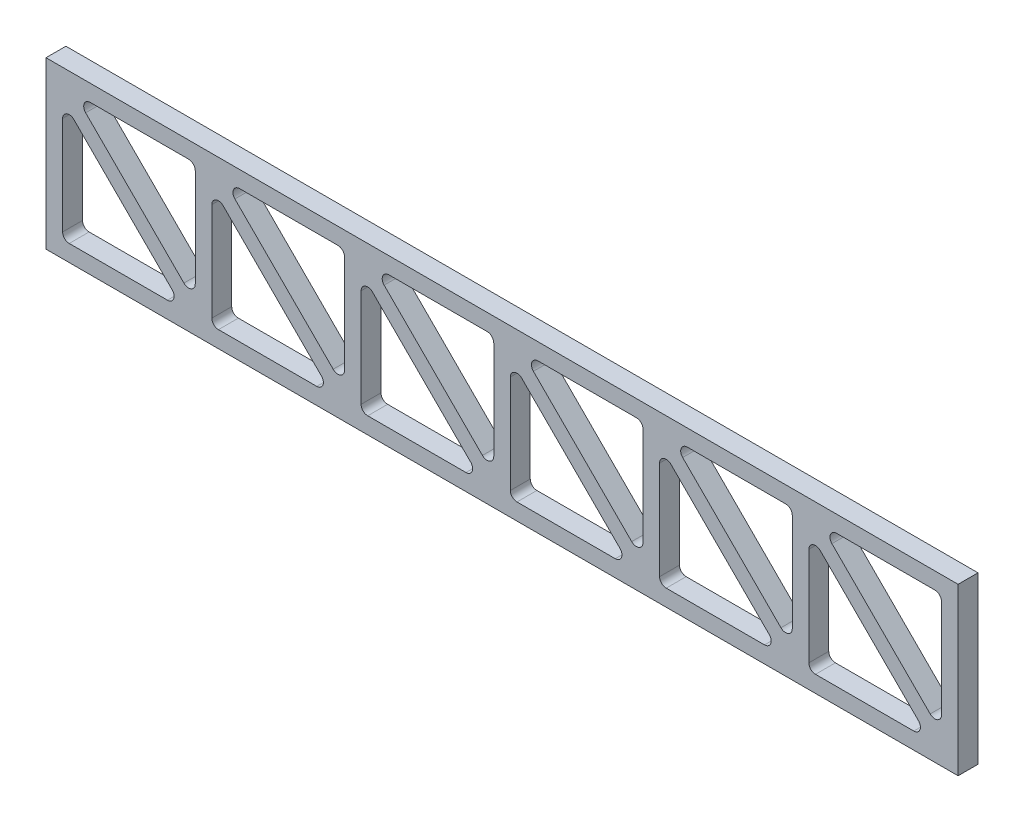
SolidWorks part; units mm, degrees
ref_plane "Front Plane" through (0, 0, 0) normal (0, 0, 1) x (1, 0, 0)
ref_plane "Top Plane" through (0, 0, 0) normal (0, 1, 0) x (1, 0, 0)
ref_plane "Right Plane" through (0, 0, 0) normal (1, 0, 0) x (0, 0, -1)
sketch "Sketch1" plane through (0, 0, 0) normal (0, 0, 1) x (1, 0, 0)
  line L0 (0, 50) -> (50, 0) construction
  line L1 (0, 0) -> (50, 0)
  line L2 (0, 0) -> (0, 50)
  line L3 (0, 50) -> (50, 50)
  line L4 (50, 0) -> (50, 50)
  line L5 (7, 5) -> (36.636, 5)
  line L6 (5, 7) -> (5, 36.636)
  line L7 (13.364, 45) -> (43, 45)
  line L8 (45, 13.364) -> (45, 43)
  line L9 (8.4142, 38.0503) -> (38.0503, 8.4142)
  line L10 (11.9497, 41.5858) -> (41.5858, 11.9497)
  arc A0 (38.0503, 8.4142) -> (36.636, 5) centre (36.636, 7) cw
  arc A1 (45, 13.364) -> (41.5858, 11.9497) centre (43, 13.364) cw
  arc A2 (13.364, 45) -> (11.9497, 41.5858) centre (13.364, 43) ccw
  arc A3 (8.4142, 38.0503) -> (5, 36.636) centre (7, 36.636) ccw
  arc A4 (7, 5) -> (5, 7) centre (7, 7) cw
  arc A5 (43, 45) -> (45, 43) centre (43, 43) cw
  dimension "D8" = 2
  dimension "D9" = 2
  dimension "D1" = 5
  dimension "D2" = 5
  dimension "D3" = 50
  dimension "D4" = 5
  dimension "D5" = 5
  dimension "D6" = 5
  dimension "D7" = 50
extrude "Boss-Extrude1" add sketch "Sketch1" along normal blind 6
pattern_linear "LPattern1" count 6 spacing 45 along (1, 0, 0) of "Boss-Extrude1"
